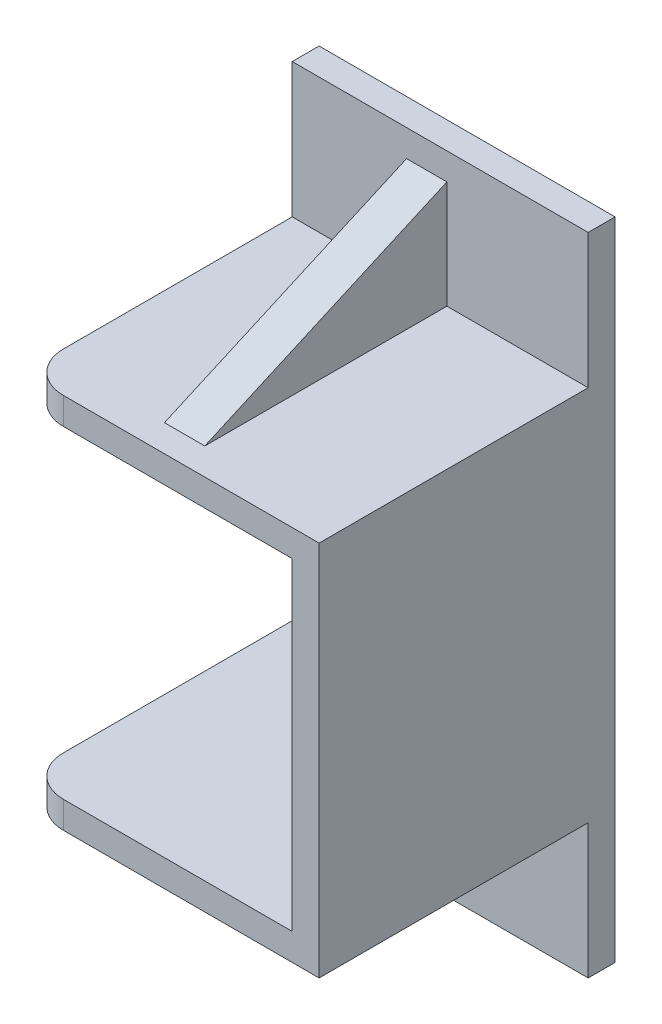
SolidWorks part; units mm, degrees
ref_plane "正面" through (0, 0, 0) normal (0, 0, 1) x (1, 0, 0)
ref_plane "平面" through (0, 0, 0) normal (0, 1, 0) x (1, 0, 0)
ref_plane "右側面" through (0, 0, 0) normal (1, 0, 0) x (0, 0, -1)
sketch "ｽｹｯﾁ2" plane through (0, 0, 0) normal (0, 0, 1) x (1, 0, 0)
  line L1 (-11, 14) -> (11, 14)
  line L2 (-11, 14) -> (-11, -14)
  line L3 (-11, -14) -> (11, -14)
  line L4 (11, 14) -> (11, -14)
  line L5 (-11, 14) -> (11, -14) construction
  line L6 (-11, -14) -> (11, 14) construction
  point P0 (0, 0)
  dimension "D1" = 22
  dimension "D2" = 28
extrude "ﾎﾞｽ - 押し出し1" add sketch "ｽｹｯﾁ2" along normal blind 22
sketch "ｽｹｯﾁ3" plane through (0, 0, 22) normal (0, 0, 1) x (1, 0, 0)
  line L1 (9, 12) -> (-9, 12)
  line L2 (9, 12) -> (9, -12)
  line L3 (9, -12) -> (-9, -12)
  line L4 (-9, 12) -> (-9, -12)
  line L5 (9, 12) -> (-9, -12) construction
  line L6 (9, -12) -> (-9, 12) construction
  point P0 (0, 0)
  dimension "D1" = 24
  dimension "D2" = 18
extrude "ｶｯﾄ - 押し出し1" cut sketch "ｽｹｯﾁ3" against normal blind 20
sketch "ｽｹｯﾁ4" plane through (0, 0, 2) normal (0, 0, 1) x (1, 0, 0)
  line L0 (9, -12) -> (9, 12) construction
  line L1 (-11, 7) -> (3, 7)
  line L2 (-11, 7) -> (-11, -7)
  line L3 (-11, -7) -> (3, -7)
  line L4 (3, 7) -> (3, -7)
  line L5 (-11, 7) -> (3, -7) construction
  line L6 (-11, -7) -> (3, 7) construction
  line L8 (-11, 14) -> (-11, -14) construction
  point P0 (-4, 0)
  dimension "D1" = 6
  dimension "D3" = 14
extrude "ｶｯﾄ - 押し出し3" cut sketch "ｽｹｯﾁ4" against normal through all
sketch "ｽｹｯﾁ6" plane through (-11, 0, 0) normal (-1, 0, 0) x (0, 0, 1)
  line L0 (22, 14) -> (22, -14) construction
  line L1 (22, 12) -> (2, 12)
  line L2 (22, 12) -> (22, -12)
  line L3 (22, -12) -> (2, -12)
  line L4 (2, 12) -> (2, -12)
  line L5 (22, 12) -> (2, -12) construction
  line L6 (22, -12) -> (2, 12) construction
  line L7 (22, 14) -> (0, 14) construction
  line L8 (22, -14) -> (0, -14) construction
  line L9 (0, 14) -> (0, 7) construction
  point P0 (12, 0)
  dimension "D1" = 2
  dimension "D2" = 2
  dimension "D3" = 2
extrude "ｶｯﾄ - 押し出し4" cut sketch "ｽｹｯﾁ6" against normal blind 5
sketch "ｽｹｯﾁ7" plane through (0, -14, 0) normal (0, -1, 0) x (1, 0, 0)
  line L0 (11, 22) -> (11, 0) construction
  line L1 (-11, 2) -> (11, 2)
  line L2 (-11, 2) -> (-11, 0)
  line L3 (-11, 0) -> (11, 0)
  line L4 (11, 2) -> (11, 0)
  line L5 (-11, 2) -> (11, 0) construction
  line L6 (-11, 0) -> (11, 2) construction
  point P0 (0, 1)
  dimension "D1" = 2
extrude "ﾎﾞｽ - 押し出し3" add sketch "ｽｹｯﾁ7" along normal blind 10
sketch "ｽｹｯﾁ8" plane through (0, 14, 0) normal (0, 1, 0) x (1, 0, 0)
  line L0 (11, 0) -> (-11, 0) construction
  line L1 (11, -2) -> (-11, -2)
  line L2 (11, -2) -> (11, 0)
  line L3 (11, 0) -> (-11, 0)
  line L4 (-11, -2) -> (-11, 0)
  line L5 (11, -2) -> (-11, 0) construction
  line L6 (11, 0) -> (-11, -2) construction
  line L7 (-11, -22) -> (-11, 0) construction
  line L8 (11, -22) -> (11, 0) construction
  point P0 (0, -1)
  dimension "D1" = 2
extrude "ﾎﾞｽ - 押し出し4" add sketch "ｽｹｯﾁ8" along normal blind 10
ref_plane "平面1" through (-1, 0, 0) normal (1, 0, 0) x (0, 0, -1)
sketch "ｽｹｯﾁ10" plane through (-1, 0, 0) normal (1, 0, 0) x (0, 0, -1)
  line L0 (-20, -14) -> (-2, -22)
  line L1 (-22, -14) -> (-2, -14) construction
  line L2 (-2, -24) -> (-2, -14) construction
  dimension "D1" = 18
  dimension "D2" = 8
rib "ﾘﾌﾞ3" sketch "ｽｹｯﾁ10" sketch "ｽｹｯﾁ10" thickness 3 extrusion direction parallel to sketch draft on no parameters "D1"=3
sketch "ｽｹｯﾁ11" plane through (-1, 0, 0) normal (1, 0, 0) x (0, 0, -1)
  line L0 (-20, 14) -> (-2, 22)
  line L1 (-22, 14) -> (-2, 14) construction
  line L2 (-2, 24) -> (-2, 14) construction
  dimension "D1" = 18
  dimension "D2" = 8
rib "ﾘﾌﾞ4" sketch "ｽｹｯﾁ11" sketch "ｽｹｯﾁ11" thickness 3 extrusion direction parallel to sketch draft on no parameters "D1"=3
fillet "ﾌｨﾚｯﾄ1" radius 3 2 edges at (-11, -13, 22) (-11, 13, 22)
